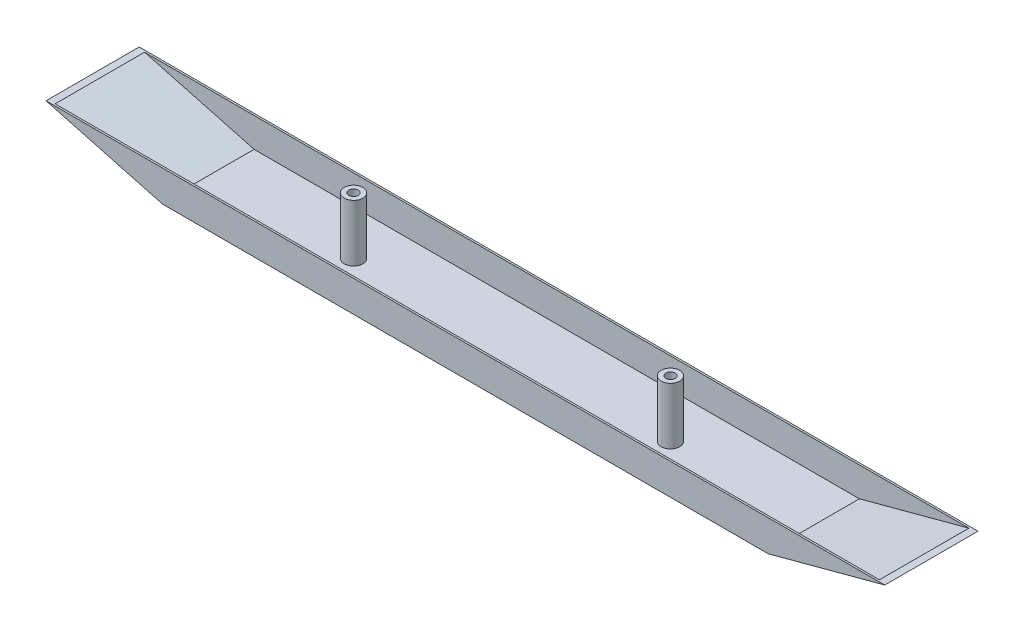
SolidWorks part; units mm, degrees
ref_plane "Front Plane" through (0, 0, 0) normal (0, 0, 1) x (1, 0, 0)
ref_plane "Top Plane" through (0, 0, 0) normal (0, 1, 0) x (1, 0, 0)
ref_plane "Right Plane" through (0, 0, 0) normal (1, 0, 0) x (0, 0, -1)
sketch "Sketch1" plane through (0, 0, 0) normal (0, 0, 1) x (1, 0, 0)
  line L0 (-162.5, 0) -> (162.5, 0)
  line L1 (162.5, 0) -> (225, 16.7468)
  line L2 (0, 0) -> (0, 35.4584) construction
  line L3 (-162.5, 0) -> (-225, 16.7468)
  line L4 (-225, 16.7468) -> (225, 16.7468)
  dimension "D1" = 162.5
  dimension "D2" = 225
  dimension "D3" = 15
extrude "Boss-Extrude1" add sketch "Sketch1" along normal blind 50
shell "Shell1" thickness 1
sketch "Sketch2" plane through (0, 0, 0) normal (0, -1, 0) x (1, 0, 0)
  line L0 (-162.5, 50) -> (162.5, 50) construction
  line L1 (-225, 50) -> (-225, 0) construction
  line L2 (225, 50) -> (225, 0) construction
  circle A0 centre (-85, 25) radius 2.5
  circle A1 centre (85, 25) radius 2.5
  dimension "D1" = 5
  dimension "D2" = 5
  dimension "D3" = 25
  dimension "D4" = 25
  dimension "D5" = 140
  dimension "D6" = 140
extrude "Cut-Extrude1" cut sketch "Sketch2" against normal blind 50
sketch "Sketch3" plane through (0, 1, 0) normal (0, 1, 0) x (1, 0, 0)
  circle A0 centre (-85, -25) radius 5
  circle A1 centre (-85, -25) radius 2.5
  circle A2 centre (85, -25) radius 5
  circle A3 centre (85, -25) radius 2.5
  dimension "D1" = 10
  dimension "D2" = 5
  dimension "D3" = 10
  dimension "D4" = 5
extrude "Boss-Extrude2" add sketch "Sketch3" along normal blind 30.5
